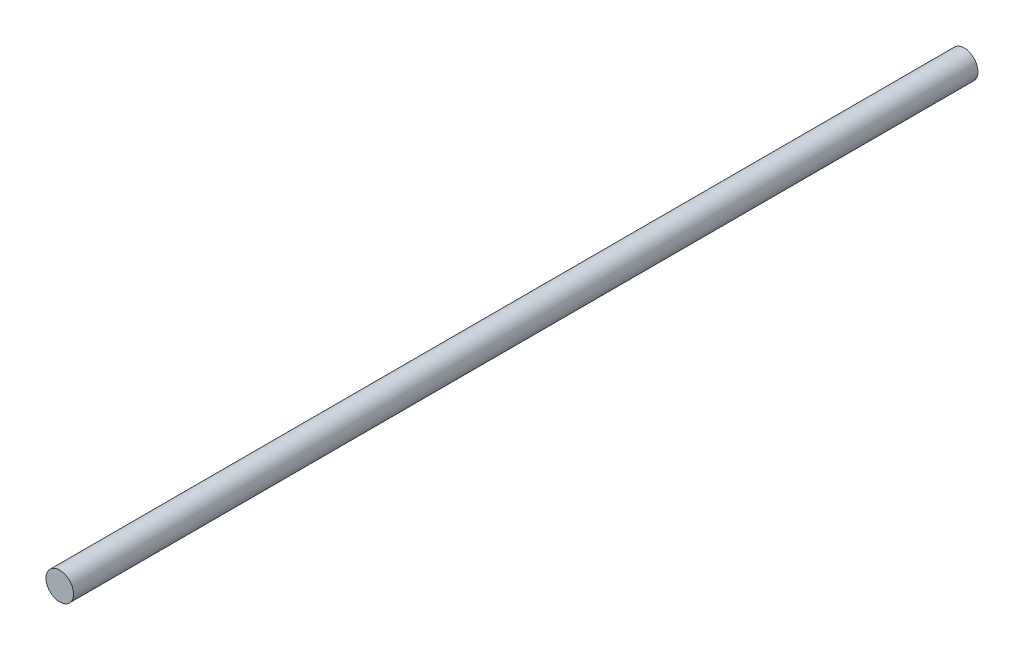
SolidWorks part; units mm, degrees
ref_plane "前视基准面" through (0, 0, 0) normal (0, 0, 1) x (1, 0, 0)
ref_plane "上视基准面" through (0, 0, 0) normal (0, 1, 0) x (1, 0, 0)
ref_plane "右视基准面" through (0, 0, 0) normal (1, 0, 0) x (0, 0, -1)
other "Configuration Table"
sketch "草图1" plane through (0, 0, 0) normal (0, 0, 1) x (1, 0, 0)
  circle A0 centre (0, 0) radius 3
  dimension "diameter" = 6
extrude "Cable_envelope" add sketch "草图1" along normal blind 196.9361
